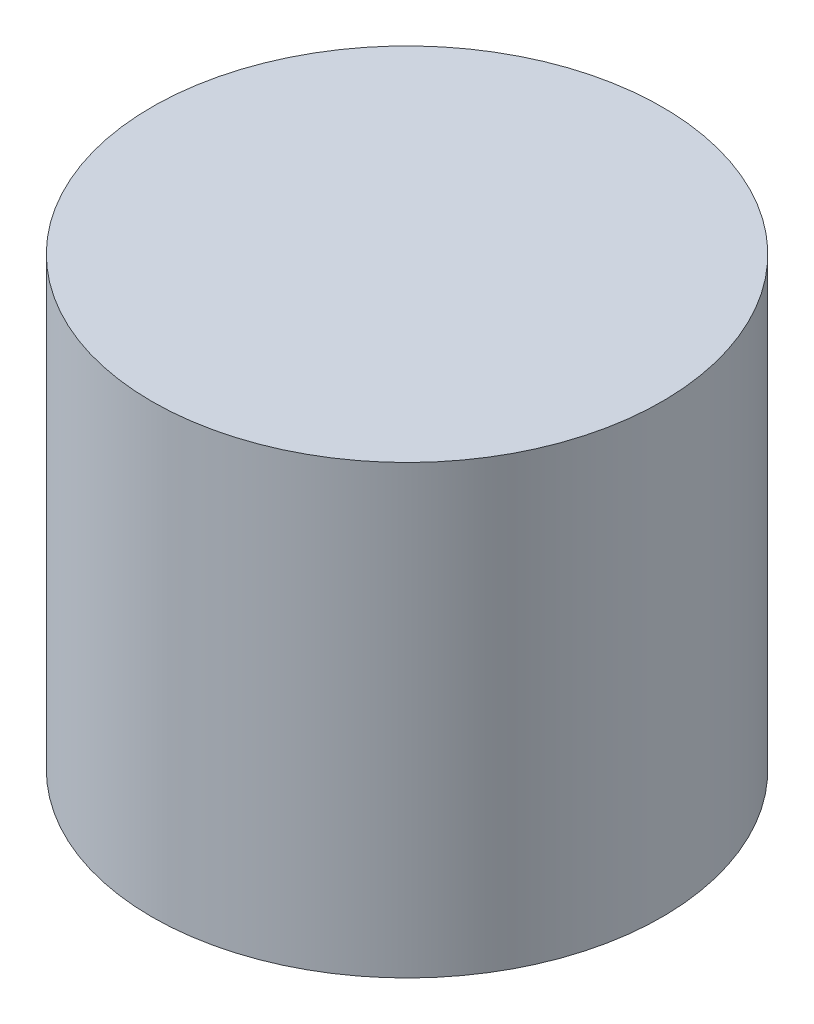
SolidWorks part; units mm, degrees
ref_plane "Front Plane" through (0, 0, 0) normal (0, 0, 1) x (1, 0, 0)
ref_plane "Top Plane" through (0, 0, 0) normal (0, 1, 0) x (1, 0, 0)
ref_plane "Right Plane" through (0, 0, 0) normal (1, 0, 0) x (0, 0, -1)
sketch "Sketch1" plane through (0, 0, 0) normal (0, 1, 0) x (1, 0, 0)
  circle A0 centre (0, 0) radius 8
  dimension "D1" = 16
extrude "Extrude1" add sketch "Sketch1" along normal blind 14
sketch "Sketch2" plane through (0, 0, 0) normal (0, -1, 0) x (1, 0, 0)
  point P0 (0, 0)
